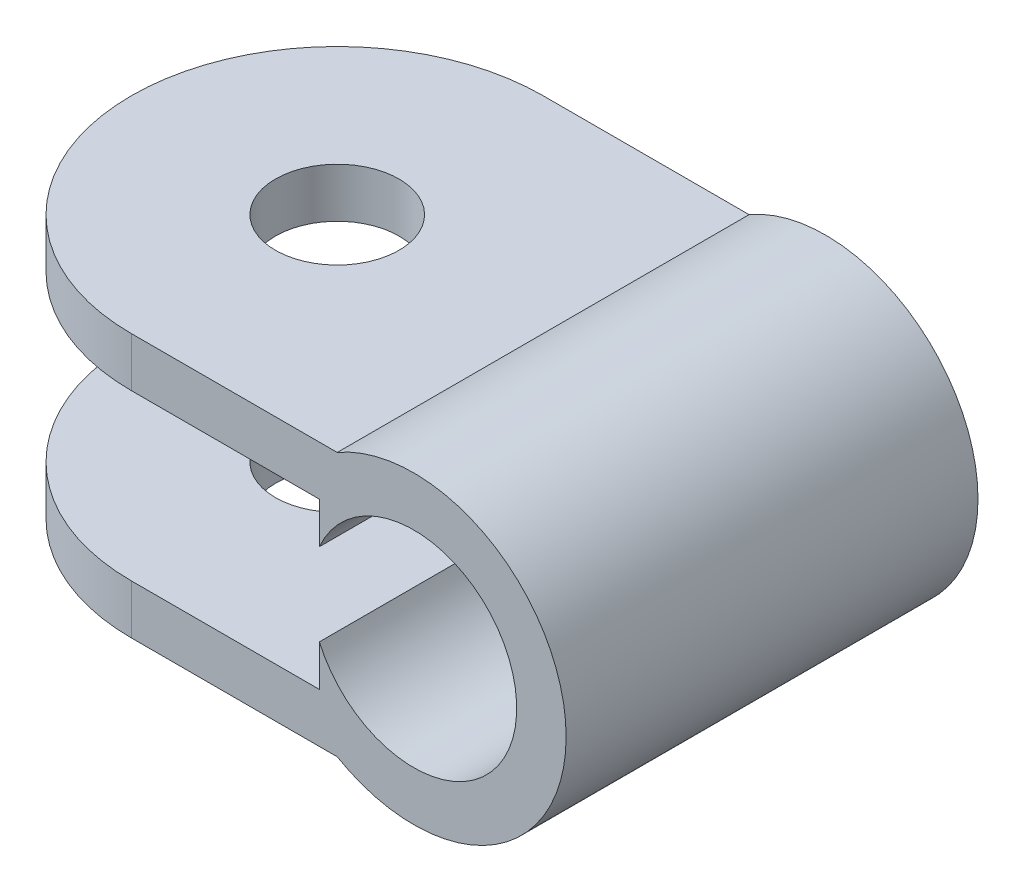
SolidWorks part; units mm, degrees
ref_plane "Front Plane" through (0, 0, 0) normal (0, 0, 1) x (1, 0, 0)
ref_plane "Top Plane" through (0, 0, 0) normal (0, 1, 0) x (1, 0, 0)
ref_plane "Right Plane" through (0, 0, 0) normal (1, 0, 0) x (0, 0, -1)
sketch "Sketch1" plane through (0, 0, 0) normal (0, 0, 1) x (1, 0, 0)
  line L1 (-11.8574, 2) -> (-11.8574, 3.2)
  line L4 (-11.8574, -2) -> (-11.8574, -3.2)
  line L6 (-15.4481, 0) -> (7.1413, 0) construction
  line L7 (-2.2913, 1) -> (-2.2913, 2)
  line L8 (-2.2913, 2) -> (-11.8574, 2)
  line L9 (-2.2913, -1) -> (-2.2913, -2)
  line L10 (-2.2913, -2) -> (-11.8574, -2)
  line L11 (-11.8574, 3.2) -> (-1.8574, 3.2)
  line L12 (-11.8574, -3.2) -> (-1.8574, -3.2)
  line L13 (-1.8574, 3.2) -> (-1.8574, -3.2) construction
  arc A2 (-1.8574, 3.2) -> (-1.8574, -3.2) centre (0, 0) cw
  arc A5 (-2.2913, 1) -> (-2.2913, -1) centre (0, 0) cw
  dimension "D1" = 1.2
  dimension "D2" = 4
  dimension "D4" = 1
  dimension "D5" = 3.7
  dimension "D3" = 2.5
  dimension "D6" = 10
extrude "Boss-Extrude1" add sketch "Sketch1" along normal mid plane 10
sketch "Sketch2" plane through (0, 3.2, 0) normal (0, 1, 0) x (1, 0, 0)
  line L0 (-11.8574, 0) -> (0, 0) construction
  line L1 (-11.8574, -5) -> (-11.8574, 5) construction
  line L2 (-1.8574, -5) -> (-11.8574, -5) construction
  line L3 (-1.8574, 5) -> (-11.8574, 5) construction
  line L4 (-6.8574, 5) -> (-12.8574, 5)
  line L5 (-12.8574, 5) -> (-12.8574, -5)
  line L6 (-12.8574, -5) -> (-6.8574, -5)
  circle A0 centre (-6.8574, 0) radius 1.5
  arc A1 (-6.8574, -5) -> (-6.8574, 5) centre (-6.8574, 0) cw
  point P7 (-7.4048, 5)
  point P14 (0, 0)
  dimension "D1" = 3
  dimension "D2" = 1
extrude "Cut-Extrude1" cut sketch "Sketch2" against normal blind 10
